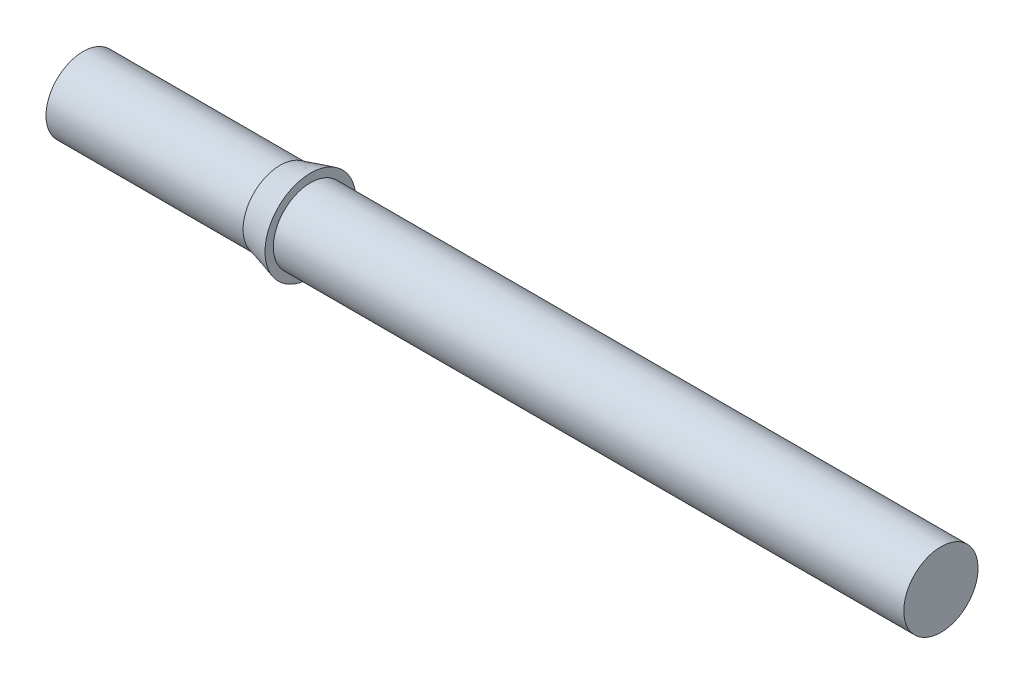
SolidWorks part; units mm, degrees
ref_plane "Front Plane" through (0, 0, 0) normal (0, 0, 1) x (1, 0, 0)
ref_plane "Top Plane" through (0, 0, 0) normal (0, 1, 0) x (1, 0, 0)
ref_plane "Right Plane" through (0, 0, 0) normal (1, 0, 0) x (0, 0, -1)
sketch "Sketch3" plane through (-52.9686, 0, 0) normal (-1, 0, 0) x (0, 0, 1)
  circle A0 centre (-1.8727, -1.6714) radius 2.5 construction
  circle A1 centre (-1.8727, -1.6714) radius 2.5 construction
  circle A2 centre (-1.8727, -1.6714) radius 2.45
extrude "Boss-Extrude1" add sketch "Sketch3" against normal up to surface (56.6 mm away)
ref_plane "Plane1" through (-39.9686, 0, 0) normal (-1, 0, 0) x (0, 0, 1)
sketch "Sketch4" plane through (-39.9686, 0, 0) normal (-1, 0, 0) x (0, 0, 1)
  circle A0 centre (-1.8727, -1.6714) radius 2.45 construction
  circle A1 centre (-1.8727, -1.6714) radius 2.45
sketch "Sketch5" plane through (-37.9686, 0, 0) normal (-1, 0, 0) x (0, 0, 1)
  circle A0 centre (-1.8727, -1.6714) radius 3
loft "Loft1" add profiles "Sketch5", "Sketch4"
ref_plane "Plane2" through (-8.3686, 0, 0) normal (-1, 0, 0) x (0, 0, 1)
sketch "Sketch7" plane through (-6.3686, 0, 0) normal (-1, 0, 0) x (0, 0, 1)
  circle A0 centre (-1.8727, -1.6714) radius 3 construction
  circle A1 centre (-1.8727, -1.6714) radius 3
